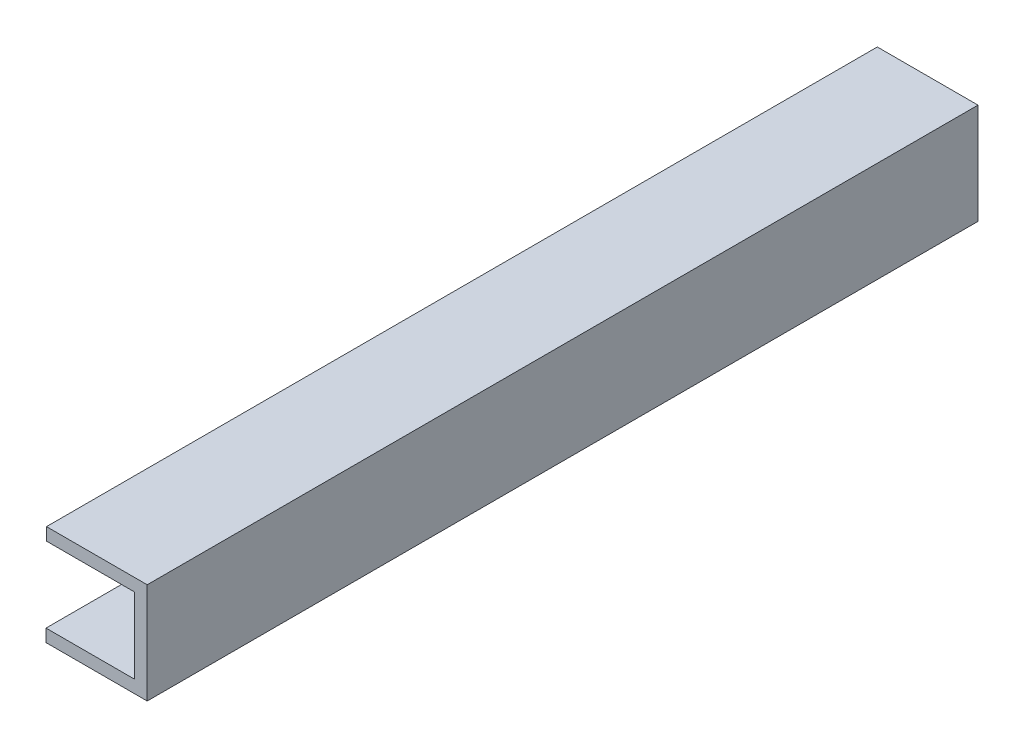
SolidWorks part; units mm, degrees
ref_plane "Front Plane" through (0, 0, 0) normal (0, 0, 1) x (1, 0, 0)
ref_plane "Top Plane" through (0, 0, 0) normal (0, 1, 0) x (1, 0, 0)
ref_plane "Right Plane" through (0, 0, 0) normal (1, 0, 0) x (0, 0, -1)
sketch "Sketch1" plane through (0, 0, 0) normal (0, 0, 1) x (1, 0, 0)
  line L0 (-35.9316, 6.8404) -> (-35.9316, 3.6654)
  line L1 (-35.9316, 3.6654) -> (-13.7066, 3.6654)
  line L2 (-13.7066, 3.6654) -> (-13.7066, -15.3846)
  line L3 (-13.7066, -15.3846) -> (-36.0586, -15.3846)
  line L4 (-36.0586, -15.3846) -> (-36.0586, -18.5596)
  line L5 (-36.0586, -18.5596) -> (-10.5316, -18.5596)
  line L6 (-10.5316, -18.5596) -> (-10.5316, 6.8404)
  line L7 (-10.5316, 6.8404) -> (-35.9316, 6.8404)
  dimension "D1" = 22.225
  dimension "D2" = 22.352
  dimension "D3" = 19.05
  dimension "D4" = 3.175
  dimension "D5" = 3.175
  dimension "D6" = 25.4
  dimension "D7" = 25.4
extrude "Boss-Extrude2" add sketch "Sketch1" along normal blind 209.55
